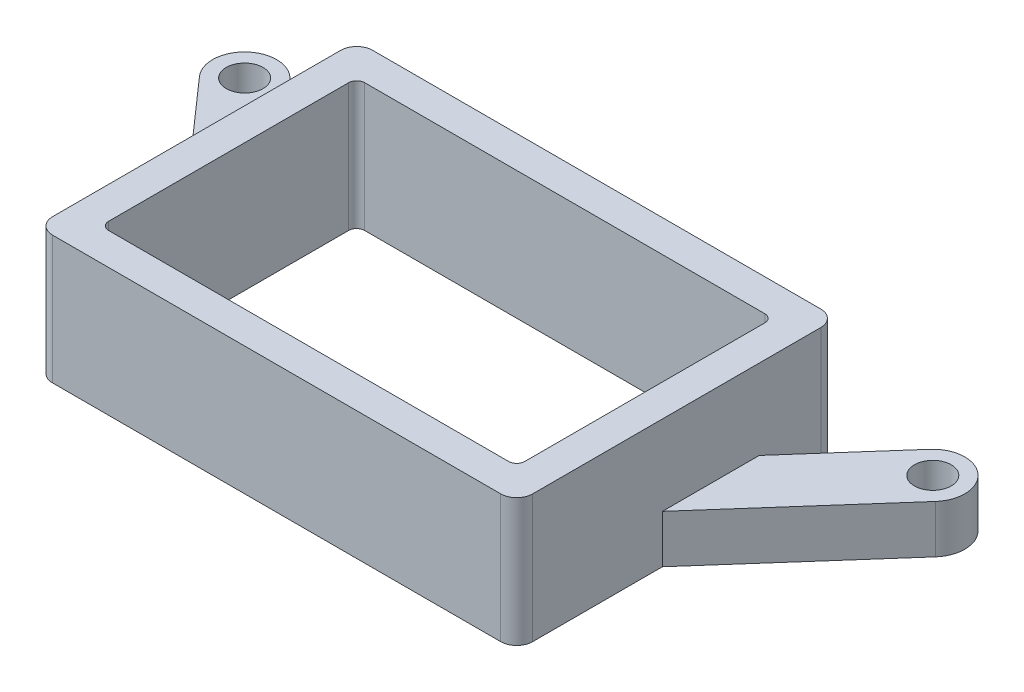
SolidWorks part; units mm, degrees
ref_plane "Front Plane" through (0, 0, 0) normal (0, 0, 1) x (1, 0, 0)
ref_plane "Top Plane" through (0, 0, 0) normal (0, 1, 0) x (1, 0, 0)
ref_plane "Right Plane" through (0, 0, 0) normal (1, 0, 0) x (0, 0, -1)
sketch "Sketch1" plane through (0, 0, 0) normal (0, 1, 0) x (1, 0, 0)
  line L0 (15, 10) -> (-15, 10)
  line L1 (13, -8) -> (-13, -8)
  line L2 (13, -8) -> (13, 8)
  line L3 (13, 8) -> (-13, 8)
  line L4 (-13, -8) -> (-13, 8)
  line L5 (13, -8) -> (-13, 8) construction
  line L6 (13, 8) -> (-13, -8) construction
  line L7 (-15, -10) -> (-15, 10)
  line L8 (15, -10) -> (-15, -10)
  line L9 (15, -10) -> (15, 10)
  line L10 (-15, -0.894) -> (-23, 8.1771)
  line L11 (-15, 5.1534) -> (-20, 10.8229)
  line L12 (-21.5, 9.5) -> (-15, 9.5) construction
  line L13 (-23, 8.1771) -> (-20, 10.8229) construction
  line L14 (0, -8) -> (0, 8) construction
  line L15 (15, -0.894) -> (23, 8.1771)
  line L16 (15, 5.1534) -> (20, 10.8229)
  arc A0 (-23, 8.1771) -> (-20, 10.8229) centre (-21.5, 9.5) cw
  circle A1 centre (-21.5, 9.5) radius 1.5 construction
  circle A2 centre (-21.5, 9.5) radius 1.15
  arc A3 (23, 8.1771) -> (20, 10.8229) centre (21.5, 9.5) ccw
  circle A4 centre (21.5, 9.5) radius 1.5 construction
  circle A5 centre (21.5, 9.5) radius 1.15
  point P0 (0, 0)
  point P15 (-20, 9.5)
  dimension "D5" = 3
  dimension "D6" = 2.3
  dimension "D7" = 2
  dimension "D1" = 26
  dimension "D2" = 16
  dimension "D4" = 21.5
  dimension "D8" = 0.5
  dimension "D3" = 2
extrude "Boss-Extrude1" add sketch "Sketch1" along normal blind 3 contours L8 L9 L0 L7 L1 L4 L3 L2 | A0 L10 L7 L11 A2 | L15 A3 L16 L9 A5
sketch "Sketch2" plane through (0, 3, 0) normal (0, 1, 0) x (1, 0, 0)
  line L1 (13, -8) -> (-13, -8)
  line L2 (13, -8) -> (13, 8)
  line L3 (13, 8) -> (-13, 8)
  line L4 (-13, -8) -> (-13, 8)
  line L5 (15, -10) -> (-15, -10)
  line L6 (15, -10) -> (15, 10)
  line L7 (15, 10) -> (-15, 10)
  line L8 (-15, -10) -> (-15, 10)
extrude "Boss-Extrude2" add sketch "Sketch2" along normal blind 5
fillet "Fillet1" radius 1 4 edges at (15, 4, 10) (15, 4, -10) (-15, 4, -10) (-15, 4, 10)
fillet "Fillet2" radius 0.5 4 edges at (13, 4, 8) (13, 4, -8) (-13, 4, 8) (-13, 4, -8)
